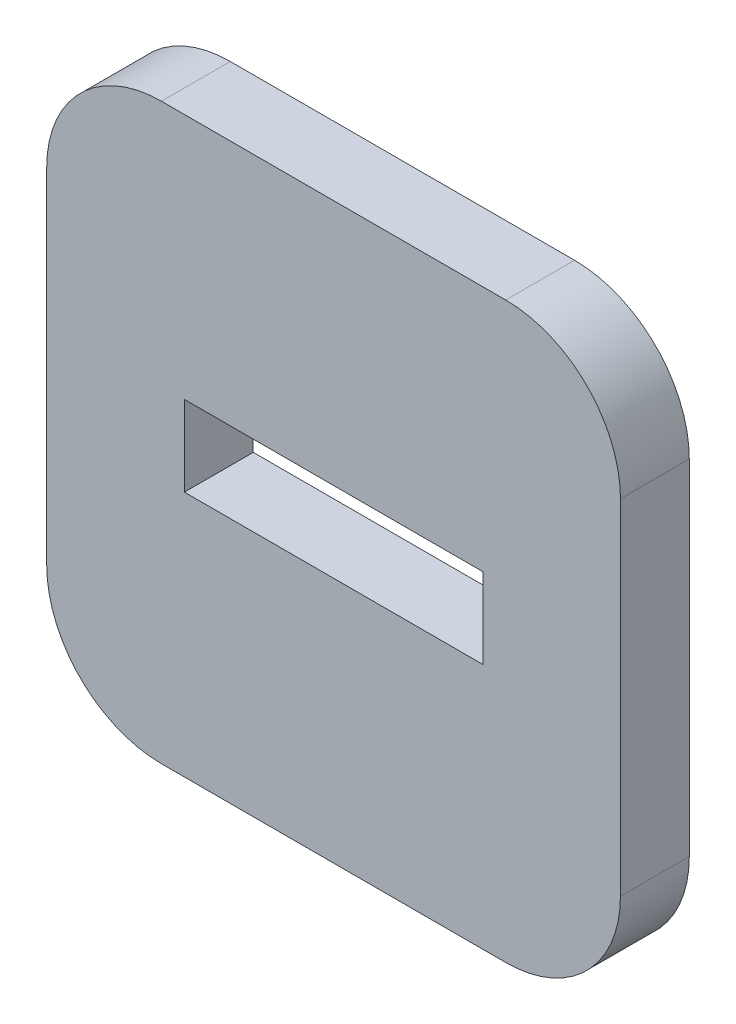
SolidWorks part; units mm, degrees
ref_plane "Front Plane" through (0, 0, 0) normal (0, 0, 1) x (1, 0, 0)
ref_plane "Top Plane" through (0, 0, 0) normal (0, 1, 0) x (1, 0, 0)
ref_plane "Right Plane" through (0, 0, 0) normal (1, 0, 0) x (0, 0, -1)
sketch "Sketch1" plane through (0, 0, 0) normal (0, 0, 1) x (1, 0, 0)
  line L0 (-1135.7574, 0) -> (48864.2426, 0) construction
  line L1 (-118.4089, -1000.0105) -> (-118.4089, 48999.9895) construction
  line L11 (-131.1089, -12.7) -> (-105.7089, -12.7)
  line L12 (-131.1089, -12.7) -> (-131.1089, 12.7)
  line L13 (-131.1089, 12.7) -> (-105.7089, 12.7)
  line L14 (-111.8049, -1.778) -> (-111.8049, 1.778)
  line L15 (-111.8049, 1.778) -> (-125.0129, 1.778)
  line L16 (-125.0129, 1.778) -> (-125.0129, -1.778)
  line L17 (-125.0129, -1.778) -> (-111.8049, -1.778)
  line L18 (-111.8049, -1.778) -> (-111.8049, 1.778)
  line L19 (-111.8049, 1.778) -> (-125.0129, 1.778)
  line L20 (-125.0129, 1.778) -> (-125.0129, -1.778)
  line L21 (-125.0129, -1.778) -> (-111.8049, -1.778)
  line L22 (-105.7089, -12.7) -> (-105.7089, 12.7)
  line L23 (-131.1089, -12.7) -> (-105.7089, 12.7) construction
  line L24 (-131.1089, 12.7) -> (-105.7089, -12.7) construction
  point P0 (-118.4089, 0)
  point P7 (-118.4089, 1.778)
  dimension "D2" = 25.4
  dimension "D3" = 25.4
  dimension "D1" = 0.254
extrude "Boss-Extrude1" add sketch "Sketch1" against normal blind 3.048 contours L13 L22 L11 L12 | L19 L20 L21 L18
fillet "Fillet1" radius 5.08 4 edges at (-131.1089, -12.7, -1.524) (-105.7089, -12.7, -1.524) (-105.7089, 12.7, -1.524) (-131.1089, 12.7, -1.524)
